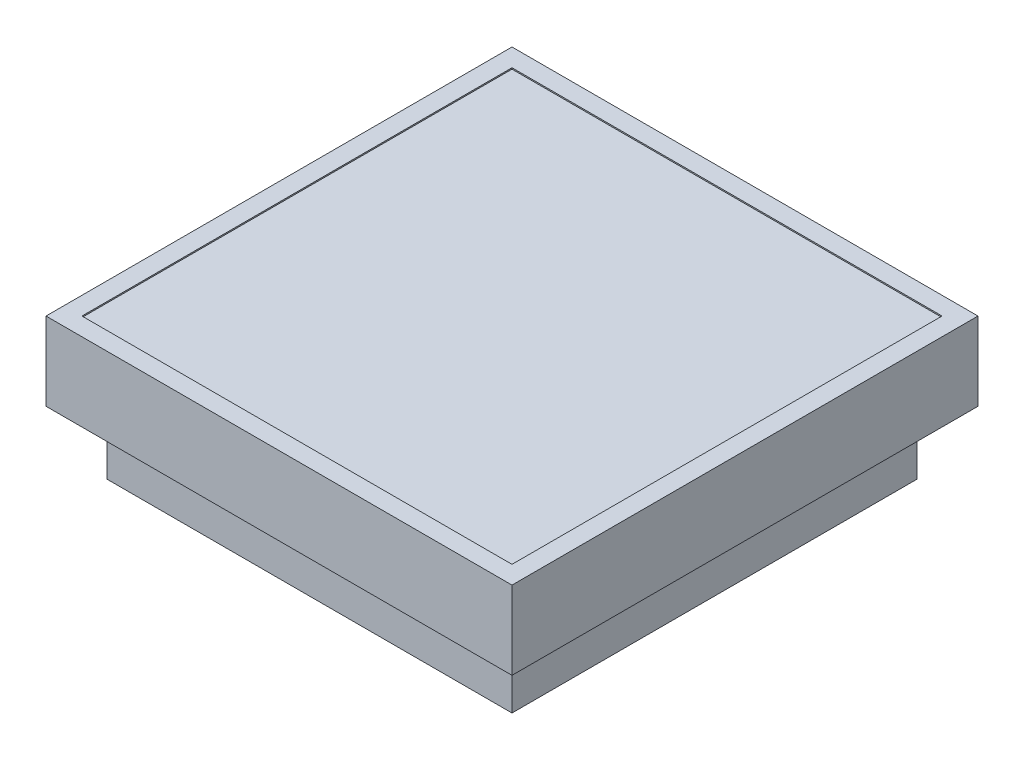
SolidWorks part; units mm, degrees
ref_plane "Front Plane" through (0, 0, 0) normal (0, 0, 1) x (1, 0, 0)
ref_plane "Top Plane" through (0, 0, 0) normal (0, 1, 0) x (1, 0, 0)
ref_plane "Right Plane" through (0, 0, 0) normal (1, 0, 0) x (0, 0, -1)
sketch "Sketch1" plane through (0, 0, 0) normal (0, 1, 0) x (1, 0, 0)
  line L1 (9.21, -9.21) -> (-9.21, -9.21)
  line L2 (9.21, -9.21) -> (9.21, 9.21)
  line L3 (9.21, 9.21) -> (-9.21, 9.21)
  line L4 (-9.21, -9.21) -> (-9.21, 9.21)
  line L5 (9.21, -9.21) -> (-9.21, 9.21) construction
  line L6 (9.21, 9.21) -> (-9.21, -9.21) construction
  point P0 (0, 0)
  dimension "D1" = 18.42
  dimension "D2" = 18.42
extrude "Boss-Extrude1" add sketch "Sketch1" along normal blind 3.09
sketch "Sketch2" plane through (0, 0, 0) normal (0, -1, 0) x (1, 0, 0)
  line L1 (8, -8) -> (-8, -8)
  line L2 (8, -8) -> (8, 8)
  line L3 (8, 8) -> (-8, 8)
  line L4 (-8, -8) -> (-8, 8)
  line L5 (8, -8) -> (-8, 8) construction
  line L6 (8, 8) -> (-8, -8) construction
  point P0 (0, 0)
  dimension "D1" = 16
  dimension "D2" = 16
extrude "Boss-Extrude2" add sketch "Sketch2" along normal blind 2.5
sketch "Sketch4" plane through (0, 3.09, 0) normal (0, 1, 0) x (1, 0, 0)
  line L1 (8.5, -8.5) -> (-8.5, -8.5)
  line L2 (8.5, -8.5) -> (8.5, 8.5)
  line L3 (8.5, 8.5) -> (-8.5, 8.5)
  line L4 (-8.5, -8.5) -> (-8.5, 8.5)
  line L5 (8.5, -8.5) -> (-8.5, 8.5) construction
  line L6 (8.5, 8.5) -> (-8.5, -8.5) construction
  point P0 (0, 0)
  dimension "D1" = 17
  dimension "D2" = 17
extrude "Cut-Extrude1" cut sketch "Sketch4" against normal blind 0.05
